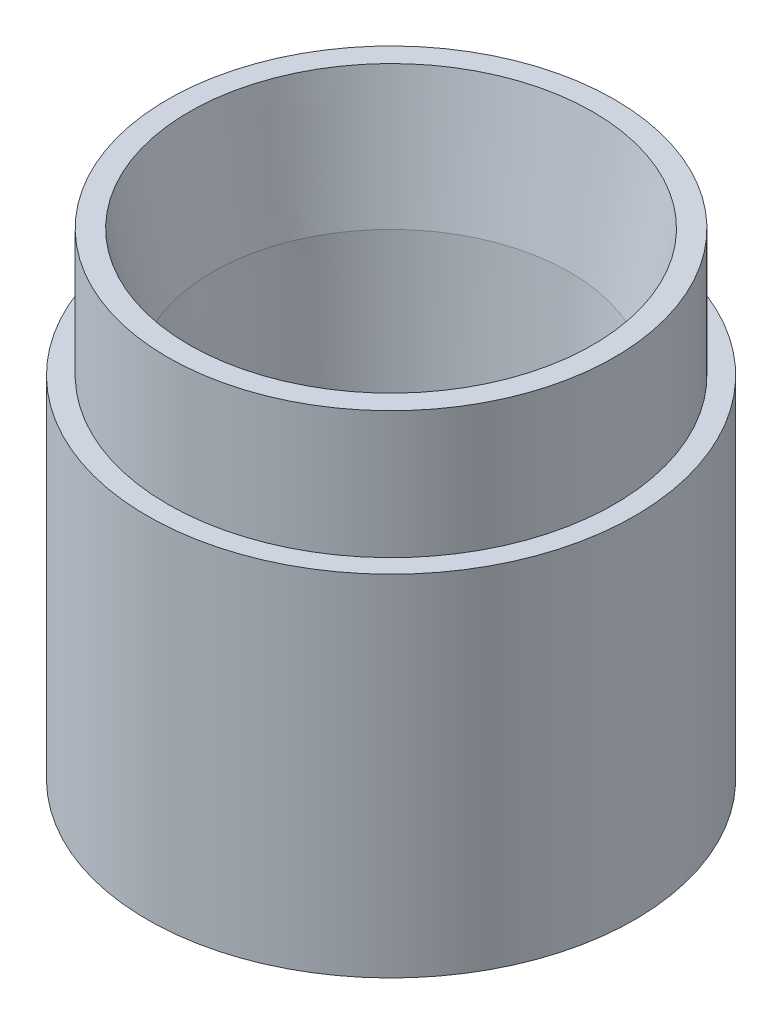
SolidWorks part; units mm, degrees
material "6061-T6 (SS)"
ref_plane "Front Plane" through (0, 0, 0) normal (0, 0, 1) x (1, 0, 0)
ref_plane "Top Plane" through (0, 0, 0) normal (0, 1, 0) x (1, 0, 0)
ref_plane "Right Plane" through (0, 0, 0) normal (1, 0, 0) x (0, 0, -1)
sketch "Sketch1" plane through (0, 0, 0) normal (0, 0, 1) x (1, 0, 0)
  line L0 (-19.939, 0) -> (19.939, 0) construction
  line L1 (19.939, 0) -> (61.1378, 58.838)
  line L2 (-19.939, 0) -> (-61.1378, 58.838)
  line L3 (-19.939, -109.3403) -> (-19.939, 58.838) construction
  line L4 (19.939, 58.838) -> (19.939, -109.3403) construction
  line L5 (19.939, 0) -> (43.18, -109.3403)
  line L6 (-19.939, 0) -> (-43.18, -109.3403)
  line L7 (0, 0) -> (0, -109.3403) construction
  line L8 (-43.18, -109.3403) -> (43.18, -109.3403) construction
  line L9 (-61.1378, 58.838) -> (61.1378, 58.838) construction
  line L10 (0, 0) -> (0, 58.838) construction
  line L11 (-69.85, 58.838) -> (69.85, 58.838) construction
  line L12 (-76.2, 58.838) -> (76.2, 58.838) construction
  line L13 (-61.1378, 58.838) -> (-69.85, 58.838)
  line L14 (-69.85, 58.838) -> (-69.85, 0)
  line L15 (-69.85, 0) -> (-76.2, 0)
  line L16 (-76.2, 0) -> (-76.2, -109.3403)
  line L17 (-76.2, -109.3403) -> (-43.18, -109.3403)
  line L18 (61.1378, 58.838) -> (69.85, 58.838)
  line L19 (69.85, 58.838) -> (69.85, 0)
  line L20 (69.85, 0) -> (76.2, 0)
  line L21 (76.2, 0) -> (76.2, -109.3403)
  line L22 (76.2, -109.3403) -> (43.18, -109.3403)
  line L23 (69.85, 39.788) -> (47.7988, 39.788)
  line L24 (-69.85, 39.788) -> (-47.7988, 39.788)
  line L25 (-76.2, 0) -> (76.2, 0) construction
  line L26 (-53.4699, 39.788) -> (-43.18, 0)
  line L27 (-43.18, 0) -> (-43.18, -76.2)
  line L28 (-43.18, -109.3403) -> (-43.18, -46.4417) construction
  line L29 (-43.18, -76.2) -> (-36.1358, -76.2)
  line L30 (-63.6778, 58.838) -> (63.6778, 58.838) construction
  line L31 (-69.85, 39.788) -> (-53.4699, 39.788) construction
  line L32 (-55.88, 0) -> (-49.53, -90.2903)
  line L33 (-63.1204, 39.788) -> (-63.1204, 35.0869) construction
  line L34 (-55.88, 0) -> (-63.1204, 39.788)
  line L35 (-43.18, -90.2903) -> (-62.0062, -90.2903) construction
  line L36 (-49.53, -90.2903) -> (-49.53, -109.3403)
  line L37 (43.18, -76.2) -> (36.1358, -76.2)
  line L38 (49.53, -90.2903) -> (49.53, -109.3403)
  line L39 (43.18, 0) -> (43.18, -76.2)
  line L40 (55.88, 0) -> (49.53, -90.2903)
  line L41 (55.88, 0) -> (63.1204, 39.788)
  line L42 (53.4699, 39.788) -> (43.18, 0)
  point P4 (0, 0)
  point P9 (-19.939, -25.2512)
  point P12 (19.939, 0)
  point P16 (0, 0)
  point P20 (0, -109.3403)
  point P22 (0, 58.838)
  point P25 (0, 58.838)
  point P37 (0, 0)
  point P39 (0, 0)
  point P46 (0, 58.838)
  dimension "D1" = 39.878
  dimension "D2" = 35
  dimension "D3" = 35
  dimension "D4" = 122.2756
  dimension "D5" = 12
  dimension "D6" = 86.36
  dimension "D7" = 139.7
  dimension "D8" = 152.4
  dimension "D9" = 19.05
  dimension "D10" = 19.05
  dimension "D11" = 152.4
  dimension "D12" = 20.5
  dimension "D13" = 12.7
  dimension "D14" = 6.35
  dimension "D15" = 127.3556
  dimension "D16" = 76.2
  dimension "D17" = 19.05
  dimension "D18" = 6.7296
ref_axis "Axis1" through (0, -117.7492, 0) along (0, 1, 0)
revolve "Revolve1" add sketch "Sketch1" angle 360 about axis through (0, -117.7492, 0) along (0, 1, 0)
